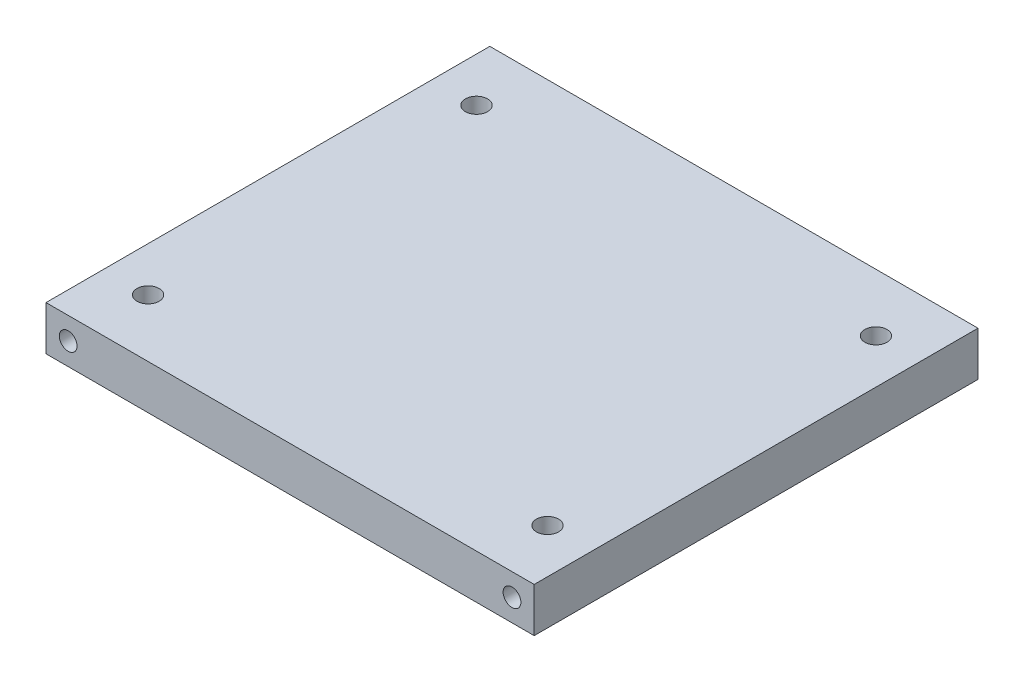
SolidWorks part; units mm, degrees
ref_plane "Front Plane" through (0, 0, 0) normal (0, 0, 1) x (1, 0, 0)
ref_plane "Top Plane" through (0, 0, 0) normal (0, 1, 0) x (1, 0, 0)
ref_plane "Right Plane" through (0, 0, 0) normal (1, 0, 0) x (0, 0, -1)
sketch "Sketch1" plane through (0, 0, 0) normal (0, 1, 0) x (1, 0, 0)
  line L1 (-55, 50) -> (55, 50)
  line L2 (-55, 50) -> (-55, -50)
  line L3 (-55, -50) -> (55, -50)
  line L4 (55, 50) -> (55, -50)
  line L5 (-55, 50) -> (55, -50) construction
  line L6 (-55, -50) -> (55, 50) construction
  point P0 (0, 0)
  dimension "D1" = 110
  dimension "D2" = 100
extrude "Boss-Extrude1" add sketch "Sketch1" along normal blind 10
sketch "Sketch2" plane through (0, 0, 50) normal (0, 0, 1) x (1, 0, 0)
  line L0 (-1050, 5) -> (48950, 5) construction
  line L1 (-55, 10) -> (-55, 0) construction
  line L2 (0, -1000) -> (0, 49000) construction
  circle A0 centre (-50, 5) radius 2
  circle A1 centre (50, 5) radius 2
  point P5 (-55, 5)
  dimension "D1" = 4
  dimension "D2" = 100
extrude "Cut-Extrude1" cut sketch "Sketch2" against normal through all
sketch "Sketch3" plane through (0, 10, 0) normal (0, 1, 0) x (1, 0, 0)
  line L0 (-1000, 0) -> (49000, 0) construction
  line L1 (0, -1000) -> (0, 49000) construction
  line L2 (-55, 50) -> (-55, -50) construction
  line L3 (-55, -50) -> (55, -50) construction
  circle A0 centre (-45, -37) radius 2.5
  circle A1 centre (45, -37) radius 2.5
  circle A2 centre (45, 37) radius 2.5
  circle A3 centre (-45, 37) radius 2.5
  dimension "D1" = 5
  dimension "D2" = 10
  dimension "D3" = 13
extrude "Cut-Extrude2" cut sketch "Sketch3" against normal blind 10
